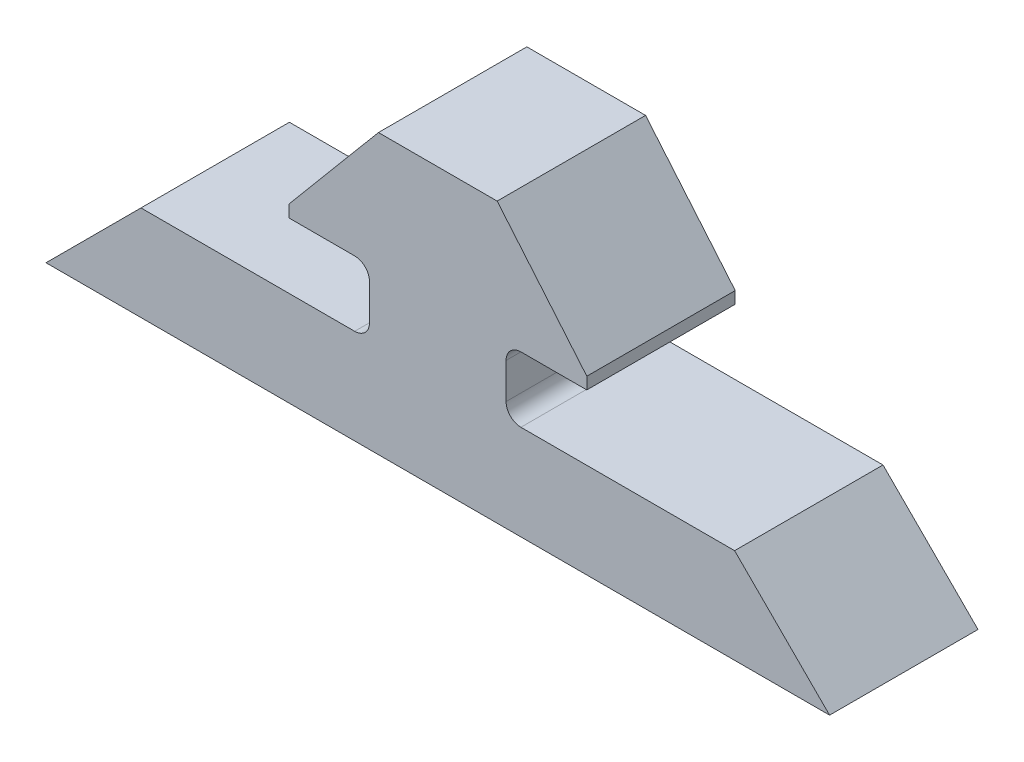
SolidWorks part; units mm, degrees
ref_plane "Front Plane" through (0, 0, 0) normal (0, 0, 1) x (1, 0, 0)
ref_plane "Top Plane" through (0, 0, 0) normal (0, 1, 0) x (1, 0, 0)
ref_plane "Right Plane" through (0, 0, 0) normal (1, 0, 0) x (0, 0, -1)
ref_plane "Plane1" through (0, 0, -3683) normal (0, 0, -1) x (-1, 0, 0)
sketch "Sketch1" plane through (0, 0, -3683) normal (0, 0, -1) x (-1, 0, 0)
  line L0 (12.7, 4.064) -> (3.556, 4.064)
  line L1 (2.921, 4.699) -> (2.921, 6.223)
  line L2 (3.556, 6.858) -> (6.3764, 6.858)
  line L3 (6.3764, 6.858) -> (6.3764, 7.366)
  line L4 (6.3764, 7.366) -> (2.54, 11.938)
  line L5 (2.54, 11.938) -> (-2.54, 11.938)
  line L6 (-2.54, 11.938) -> (-6.3764, 7.366)
  line L7 (-6.3764, 7.366) -> (-6.3764, 6.858)
  line L8 (-6.3764, 6.858) -> (-3.556, 6.858)
  line L9 (-2.921, 6.223) -> (-2.921, 4.699)
  line L10 (-3.556, 4.064) -> (-12.7, 4.064)
  line L12 (-12.7, 0) -> (12.7, 0)
  line L14 (-12.7, 4.064) -> (-16.764, 0)
  line L15 (-16.764, 0) -> (-12.7, 0)
  line L16 (12.7, 4.064) -> (16.764, 0)
  line L17 (16.764, 0) -> (12.7, 0)
  arc A0 (3.556, 4.064) -> (2.921, 4.699) centre (3.556, 4.699) cw
  arc A1 (2.921, 6.223) -> (3.556, 6.858) centre (3.556, 6.223) cw
  arc A2 (-3.556, 6.858) -> (-2.921, 6.223) centre (-3.556, 6.223) cw
  arc A3 (-2.921, 4.699) -> (-3.556, 4.064) centre (-3.556, 4.699) cw
extrude "Boss-Extrude8" add sketch "Sketch1" along normal blind 6.35
